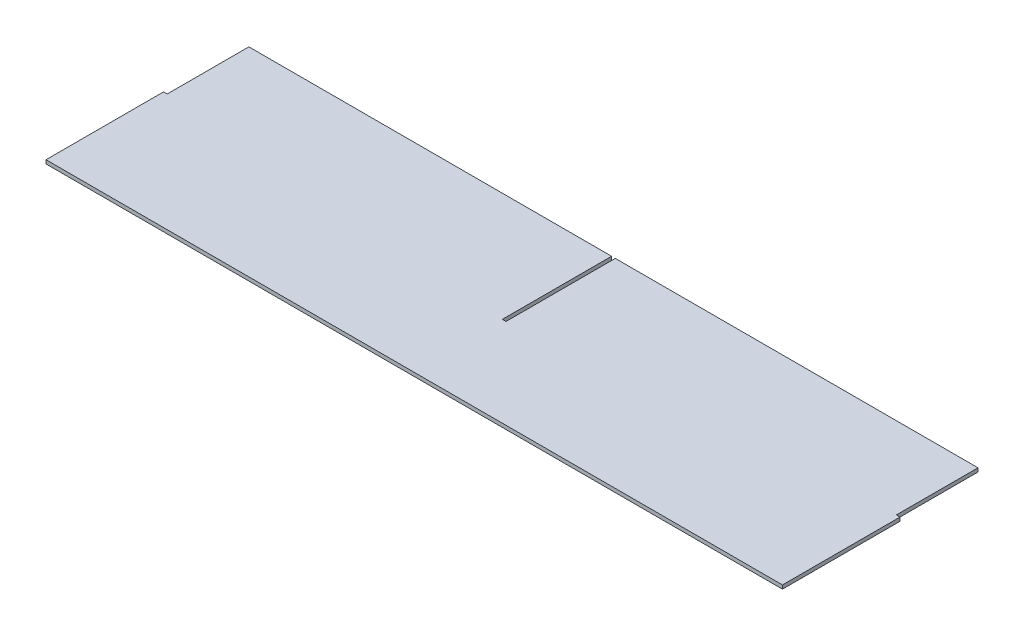
SolidWorks part; units mm, degrees
material "6061-T6 (SS)"
ref_plane "X-Y Datum" through (0, 0, 0) normal (0, 0, 1) x (1, 0, 0)
ref_plane "X-Z Datum" through (0, 0, 0) normal (0, 1, 0) x (1, 0, 0)
ref_plane "Y-Z Datum" through (0, 0, 0) normal (1, 0, 0) x (0, 0, -1)
sketch "Sketch1" plane through (0, 0, 0) normal (0, 1, 0) x (1, 0, 0)
  line L1 (0, 0) -> (636.2598, 0)
  line L2 (0, 0) -> (0, 172.0926)
  line L3 (0, 172.0926) -> (636.2598, 172.0926)
  line L4 (636.2598, 0) -> (636.2598, 172.0926)
extrude "Boss-Extrude1" add sketch "Sketch1" along normal blind 3.175 contours L3 L4 L1 L2
sketch "Sketch2" plane through (0, 0, -172.0926) normal (0, 0, -1) x (-1, 0, 0)
  line L3 (-319.7174, 3.175) -> (-316.5424, 3.175) construction
  line L4 (-319.7174, 3.175) -> (-316.5424, 3.175)
  line L5 (-319.7174, 3.175) -> (-319.7174, 0)
  line L6 (-319.7174, 0) -> (-316.5424, 0)
  line L7 (-316.5424, 3.175) -> (-316.5424, 0)
  line L9 (-319.7174, 0) -> (-316.5424, 0) construction
extrude "Cut-Extrude1" cut sketch "Sketch2" against normal blind 94.3661
sketch "Sketch3" plane through (0, 0, -172.0926) normal (0, 0, 1) x (1, 0, 0)
  line L0 (0, 0) -> (636.2598, 0) construction
  line L1 (0, 3.175) -> (3.175, 3.175)
  line L2 (0, 3.175) -> (0, 0)
  line L3 (0, 0) -> (3.175, 0)
  line L4 (3.175, 3.175) -> (3.175, 0)
  line L6 (636.2598, 3.175) -> (633.0848, 3.175)
  line L7 (636.2598, 3.175) -> (636.2598, 0)
  line L8 (636.2598, 0) -> (633.0848, 0)
  line L9 (633.0848, 3.175) -> (633.0848, 0)
extrude "Cut-Extrude5" cut sketch "Sketch3" along normal blind 70.4926
